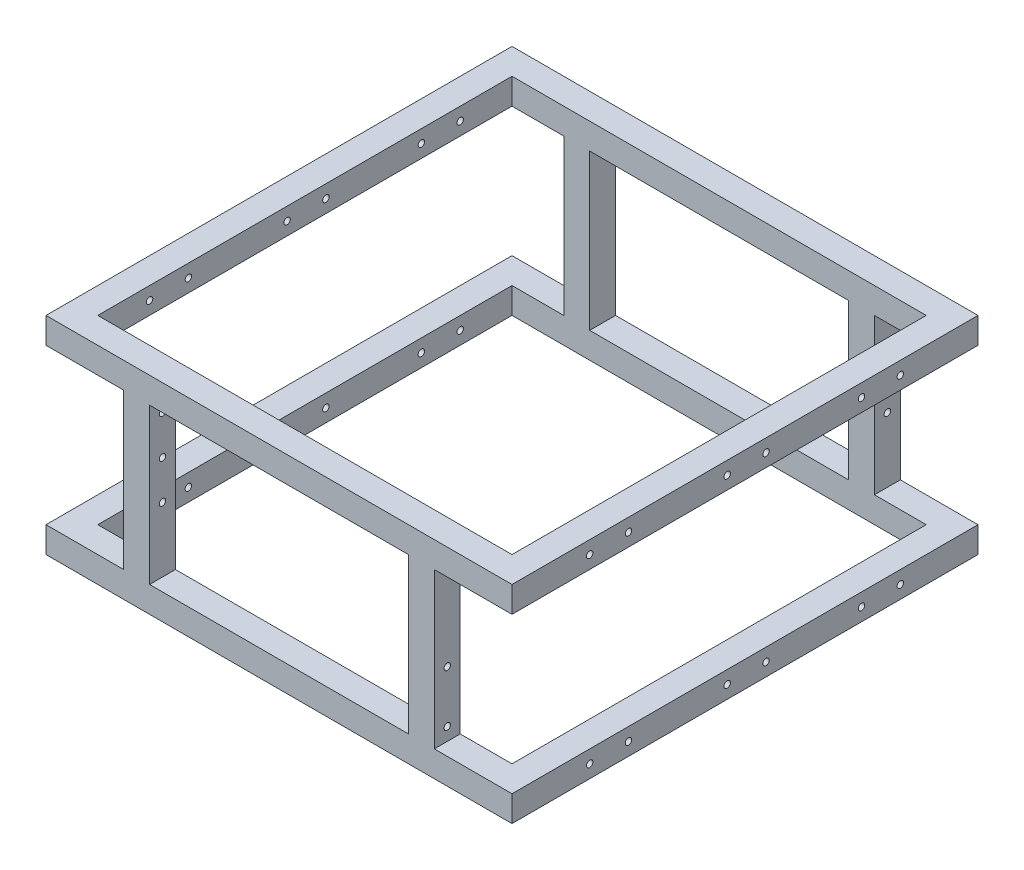
SolidWorks part; units mm, degrees
ref_plane "Front Plane" through (0, 0, 0) normal (0, 0, 1) x (1, 0, 0)
ref_plane "Top Plane" through (0, 0, 0) normal (0, 1, 0) x (1, 0, 0)
ref_plane "Right Plane" through (0, 0, 0) normal (1, 0, 0) x (0, 0, -1)
sketch "Sketch1" plane through (0, 0, 0) normal (0, 1, 0) x (1, 0, 0)
  line L1 (-228.6, 228.6) -> (228.6, 228.6)
  line L2 (-228.6, 228.6) -> (-228.6, -228.6)
  line L3 (-228.6, -228.6) -> (228.6, -228.6)
  line L4 (228.6, 228.6) -> (228.6, -228.6)
  line L5 (-228.6, 228.6) -> (228.6, -228.6) construction
  line L6 (-228.6, -228.6) -> (228.6, 228.6) construction
  line L7 (-203.2, 203.2) -> (203.2, 203.2)
  line L8 (-203.2, 203.2) -> (-203.2, -203.2)
  line L9 (-203.2, -203.2) -> (203.2, -203.2)
  line L10 (203.2, 203.2) -> (203.2, -203.2)
  line L11 (-203.2, 203.2) -> (203.2, -203.2) construction
  line L12 (-203.2, -203.2) -> (203.2, 203.2) construction
  point P0 (0, 0)
  point P6 (0, 0)
  dimension "D1" = 457.2
  dimension "D2" = 457.2
  dimension "D3" = 406.4
extrude "Boss-Extrude1" add sketch "Sketch1" along normal blind 203.2
sketch "Sketch2" plane through (0, 0, 228.6) normal (0, 0, 1) x (1, 0, 0)
  line L0 (228.6, 203.2) -> (228.6, 0) construction
  line L1 (-127, 177.8) -> (127, 177.8)
  line L2 (-127, 177.8) -> (-127, 25.4)
  line L3 (-127, 25.4) -> (127, 25.4)
  line L4 (127, 177.8) -> (127, 25.4)
  line L5 (-127, 177.8) -> (127, 25.4) construction
  line L6 (-127, 25.4) -> (127, 177.8) construction
  line L7 (-228.6, 203.2) -> (-228.6, 0) construction
  line L8 (-228.6, 203.2) -> (228.6, 203.2) construction
  line L9 (-228.6, 0) -> (228.6, 0) construction
  line L10 (0, 203.2) -> (0, 0) construction
  line L11 (228.6, 177.8) -> (228.6, 25.4)
  line L12 (-228.6, 177.8) -> (-152.4, 177.8)
  line L13 (-228.6, 177.8) -> (-228.6, 25.4)
  line L14 (-228.6, 25.4) -> (-152.4, 25.4)
  line L15 (-152.4, 177.8) -> (-152.4, 25.4)
  line L16 (228.6, 177.8) -> (152.4, 177.8)
  line L17 (152.4, 177.8) -> (152.4, 25.4)
  line L18 (228.6, 25.4) -> (152.4, 25.4)
  point P0 (0, 101.6)
  dimension "D1" = 25.4
  dimension "D2" = 101.6
  dimension "D3" = 25.4
  dimension "D4" = 25.4
  dimension "D5" = 25.4
extrude "Cut-Extrude3" cut sketch "Sketch2" against normal up to surface (431.8 mm away) up to face at (0, 101.6, -203.2)
sketch "Sketch4" plane through (0, 0, -228.6) normal (0, 0, -1) x (-1, 0, 0)
  line L0 (0, 203.2) -> (0, 0) construction
  line L1 (-228.6, 203.2) -> (228.6, 203.2) construction
  line L2 (-228.6, 177.8) -> (-228.6, 25.4) construction
  line L3 (-228.6, 177.8) -> (-228.6, 25.4) construction
  line L4 (228.6, 25.4) -> (228.6, 177.8) construction
  line L5 (228.6, 25.4) -> (228.6, 177.8) construction
  line L6 (228.6, 177.8) -> (228.6, 25.4)
  line L7 (-228.6, 177.8) -> (-12.7, 177.8)
  line L8 (-228.6, 177.8) -> (-228.6, 25.4)
  line L9 (-228.6, 25.4) -> (-12.7, 25.4)
  line L10 (-12.7, 177.8) -> (-12.7, 25.4)
  line L11 (228.6, 177.8) -> (12.7, 177.8)
  line L12 (12.7, 177.8) -> (12.7, 25.4)
  line L13 (228.6, 25.4) -> (12.7, 25.4)
  dimension "D1" = 12.7
extrude "Cut-Extrude4" cut sketch "Sketch4" against normal up to surface (25.4 mm away) up to face at (0, 101.6, -203.2)
sketch "Sketch6" plane through (152.4, 0, 0) normal (1, 0, 0) x (0, 0, -1)
  line L0 (-203.2, 25.4) -> (-228.6, 25.4) construction
  line L1 (-228.6, 177.8) -> (-228.6, 25.4) construction
  circle A0 centre (-215.9, 38.1) radius 3.175
  circle A4 centre (-215.9, 88.9) radius 3.175
  dimension "D1" = 6.35
  dimension "D2" = 12.7
  dimension "D3" = 12.7
  dimension "D4" = 2
extrude "Cut-Extrude5" cut sketch "Sketch6" against normal up to surface (25.4 mm away) up to face at (127, 101.6, 215.9)
sketch "Sketch7" plane through (-152.4, 0, 0) normal (-1, 0, 0) x (0, 0, 1)
  line L0 (203.2, 177.8) -> (203.2, 25.4) construction
  line L2 (55, 0) -> (-55, 0) construction
  circle A2 centre (215.9, 165.1) radius 3.175
  circle A3 centre (215.9, 127) radius 3.175
  circle A4 centre (215.9, 88.9) radius 3.175
  dimension "D1" = 6.35
  dimension "D2" = 165.1
  dimension "D3" = 12.7
  dimension "D5" = 38.1
  dimension "D4" = 3
extrude "Cut-Extrude6" cut sketch "Sketch7" against normal up to surface (25.4 mm away) up to face at (-127, 101.6, 215.9)
sketch "Sketch8" plane through (228.6, 0, 0) normal (1, 0, 0) x (0, 0, -1)
  line L0 (228.6, 203.2) -> (228.6, 177.8) construction
  line L1 (228.6, 177.8) -> (-228.6, 177.8) construction
  line L2 (-228.6, 0) -> (228.6, 0) construction
  circle A0 centre (152.4, 190.5) radius 3.175
  circle A1 centre (114.3, 190.5) radius 3.175
  circle A2 centre (-152.4, 190.5) radius 3.175
  circle A3 centre (-114.3, 190.5) radius 3.175
  circle A4 centre (152.4, 12.7) radius 3.175
  circle A5 centre (114.3, 12.7) radius 3.175
  circle A6 centre (-114.3, 12.7) radius 3.175
  circle A7 centre (-152.4, 12.7) radius 3.175
  dimension "D1" = 6.35
  dimension "D7" = 6.35
  dimension "D2" = 76.2
  dimension "D3" = 38.1
  dimension "D4" = 228.6
  dimension "D5" = 38.1
  dimension "D6" = 12.7
  dimension "D8" = 12.7
extrude "Cut-Extrude7" cut sketch "Sketch8" against normal up to surface (457.2 mm away) up to face at (-228.6, 190.5, 0)
sketch "Sketch10" plane through (228.6, 0, 0) normal (1, 0, 0) x (0, 0, -1)
  line L0 (228.6, 177.8) -> (-228.6, 177.8) construction
  circle A0 centre (-17.4625, 190.5) radius 3.175
  circle A1 centre (-114.3, 190.5) radius 3.175 construction
  dimension "D1" = 6.35
  dimension "D2" = 96.8375
  dimension "D3" = 12.7
extrude "Cut-Extrude8" cut sketch "Sketch10" against normal through all
pattern_linear "LPattern1" count 2 spacing 38.1 along (0, 0, -1) count 2 spacing 177.8 along (0, -1, 0) of "Cut-Extrude8"
sketch "Sketch12" plane through (0, 0, -228.6) normal (0, 0, -1) x (-1, 0, 0)
  line L1 (-12.7, 177.8) -> (12.7, 177.8)
  line L2 (-12.7, 177.8) -> (-12.7, 25.4)
  line L3 (-12.7, 25.4) -> (12.7, 25.4)
  line L4 (12.7, 177.8) -> (12.7, 25.4)
extrude "Cut-Extrude9" cut sketch "Sketch12" against normal blind 25.4
sketch "Sketch13" plane through (0, 0, -228.6) normal (0, 0, -1) x (-1, 0, 0)
  line L0 (-228.6, 25.4) -> (228.6, 25.4) construction
  line L1 (-127, 177.8) -> (-152.4, 177.8)
  line L2 (-127, 177.8) -> (-127, 25.4)
  line L3 (-127, 25.4) -> (-152.4, 25.4)
  line L4 (-152.4, 177.8) -> (-152.4, 25.4)
  line L5 (-152.4, 25.4) -> (-152.4, 177.8) construction
  line L7 (152.4, 177.8) -> (127, 177.8)
  line L8 (152.4, 177.8) -> (152.4, 25.4)
  line L9 (152.4, 25.4) -> (127, 25.4)
  line L10 (127, 177.8) -> (127, 25.4)
extrude "Boss-Extrude2" add sketch "Sketch13" against normal blind 25.4
sketch "Sketch14" plane through (127, 0, 0) normal (-1, 0, 0) x (0, 0, 1)
  line L0 (-228.6, 25.4) -> (-203.2, 25.4)
  line L1 (-215.9, 25.4) -> (-215.9, 88.9)
  line L2 (-215.9, 88.9) -> (-215.9, 127)
  circle A0 centre (-215.9, 127) radius 3.175
  circle A1 centre (-215.9, 88.9) radius 3.175
  dimension "D3" = 6.35
  dimension "D4" = 6.35
  dimension "D1" = 63.5
  dimension "D2" = 38.1
extrude "Cut-Extrude11" cut sketch "Sketch14" against normal up to surface (25.4 mm away) up to face at (152.4, 101.6, -215.9)
